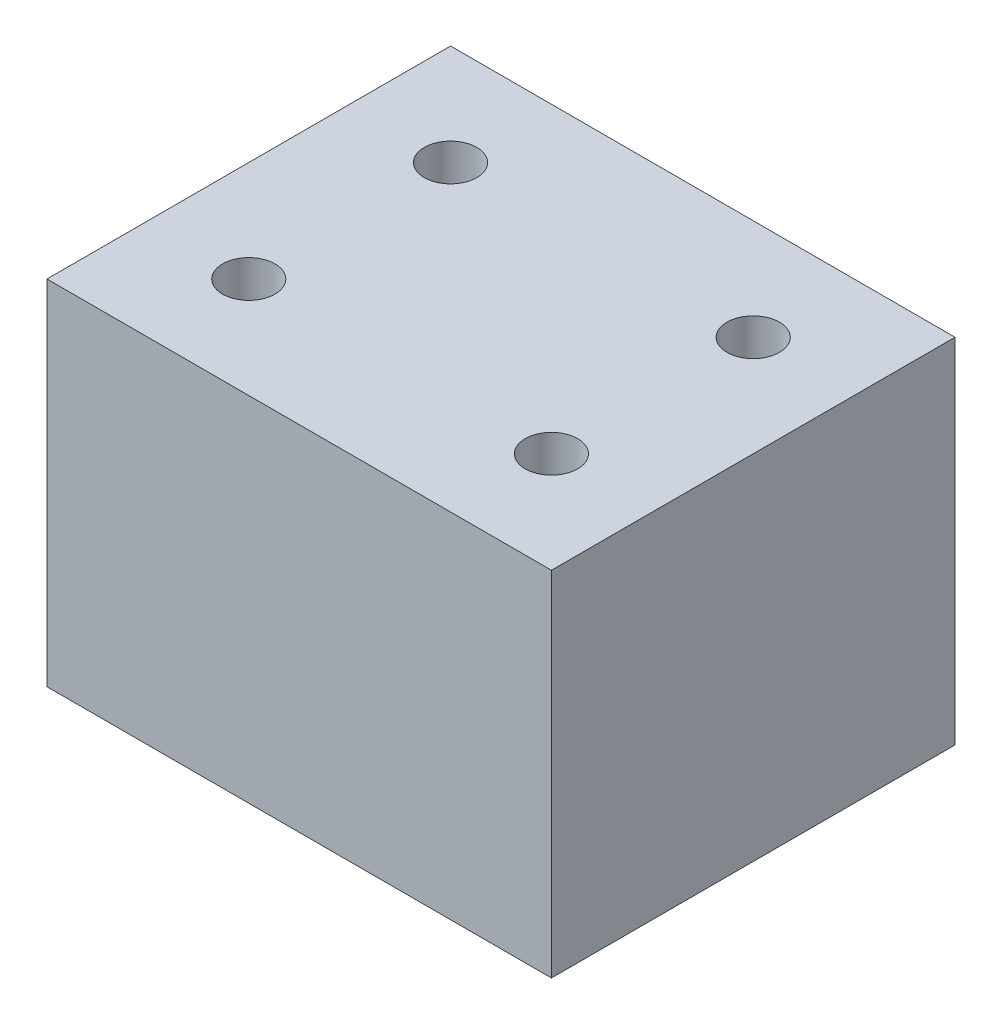
SolidWorks part; units mm, degrees
ref_plane "前视基准面" through (0, 0, 0) normal (0, 0, 1) x (1, 0, 0)
ref_plane "上视基准面" through (0, 0, 0) normal (0, 1, 0) x (1, 0, 0)
ref_plane "右视基准面" through (0, 0, 0) normal (1, 0, 0) x (0, 0, -1)
sketch "草图1" plane through (0, 0, 0) normal (0, 1, 0) x (1, 0, 0)
  line L1 (-25, 20) -> (25, 20)
  line L2 (-25, 20) -> (-25, -20)
  line L3 (-25, -20) -> (25, -20)
  line L4 (25, 20) -> (25, -20)
  line L5 (-25, 20) -> (25, -20) construction
  line L6 (-25, -20) -> (25, 20) construction
  point P0 (0, 0)
extrude "凸台-拉伸1" add sketch "草图1" along normal blind 35
sketch "草图2" plane through (0, 35, 0) normal (0, 1, 0) x (1, 0, 0)
  circle A0 centre (-15, -10) radius 2.6
  circle A1 centre (15, -10) radius 2.6
  circle A2 centre (-15, 10) radius 2.6
  circle A3 centre (15, 10) radius 2.6
  dimension "D1" = 2
  dimension "D2" = 2
extrude "切除-拉伸1" cut sketch "草图2" against normal through all
